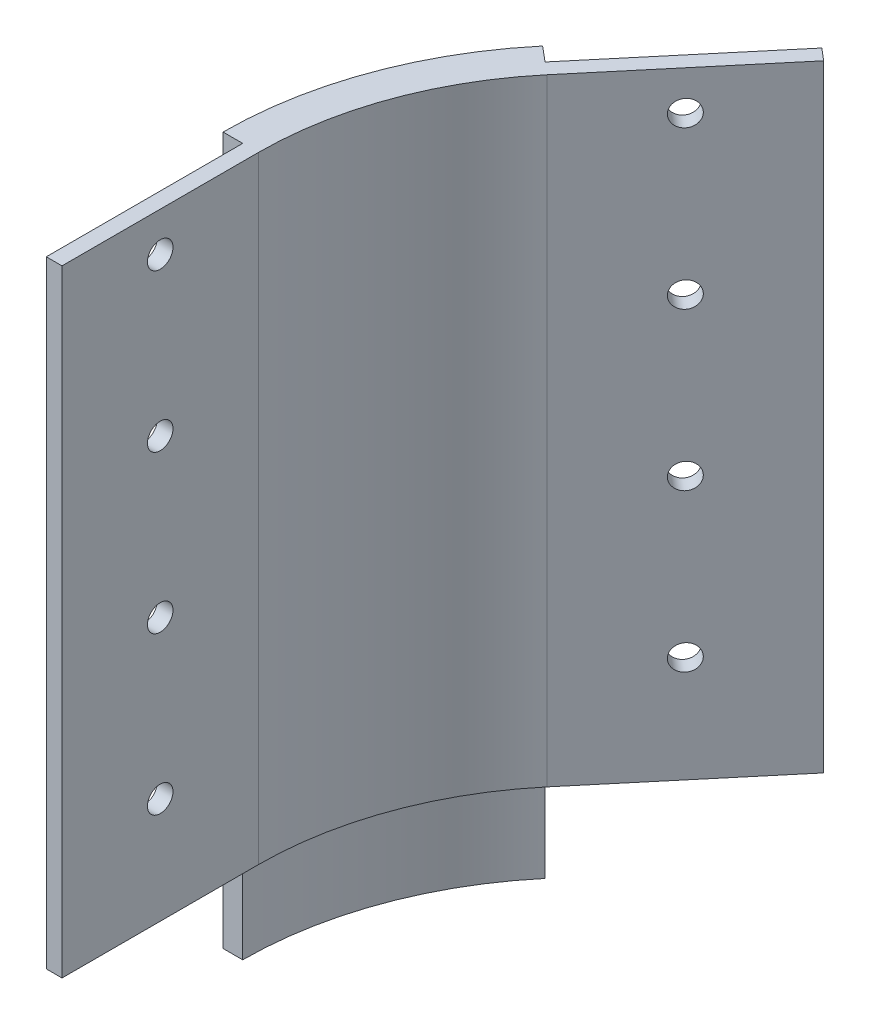
SolidWorks part; units mm, degrees
material "Custom Plastic"
ref_plane "Front Plane" through (0, 0, 0) normal (0, 0, 1) x (1, 0, 0)
ref_plane "Top Plane" through (0, 0, 0) normal (0, 1, 0) x (1, 0, 0)
ref_plane "Right Plane" through (0, 0, 0) normal (1, 0, 0) x (0, 0, -1)
sketch "Sketch1" plane through (0, 0, 0) normal (0, 1, 0) x (1, 0, 0)
  line L0 (0, 0) -> (65.2704, 0) construction
  line L1 (65.2704, 0) -> (65.2704, 50) construction
  line L2 (0, 0) -> (0, -10) construction
  line L3 (18.1985, 50) -> (-23.7565, 0) construction
  line L4 (10, 0) -> (-10, 0)
  line L5 (25.859, 43.5721) -> (10.5381, 56.4279)
  arc A0 (0, 0) -> (18.1985, 50) centre (77.7862, 0) cw construction
  arc A1 (10, 0) -> (25.859, 43.5721) centre (77.7862, 0) cw
  arc A2 (-10, 0) -> (10.5381, 56.4279) centre (77.7862, 0) cw
  circle A3 centre (0.6455, 10) radius 2.6
  circle A4 centre (4.6911, 26.6044) radius 2.6
  circle A5 centre (12.2651, 41.9247) radius 2.6
  circle A7 centre (23.0019, 55.2211) radius 2.6 [skipped]
  point P24 (77.7862, 0)
  dimension "D6" = 5.2
  dimension "D9" = 10
  dimension "D1" = 10
  dimension "D2" = 50
  dimension "D3" = 50
  dimension "D7" = 10
  dimension "D8" = 4
  dimension "D4" = 10
  dimension "D5" = 10
extrude "Boss-Extrude1" add sketch "Sketch1" along normal blind 20
sketch "Sketch2" plane through (0, 20, 0) normal (0, 1, 0) x (1, 0, 0)
  line L0 (6.7078, 59.6418) -> (10.5381, 56.4279)
  line L1 (-15, 0) -> (-10, 0)
  arc A1 (10.5381, 56.4279) -> (-10, 0) centre (77.7862, 0) ccw construction
  arc A2 (6.7078, 59.6418) -> (-15, 0) centre (77.7862, 0) ccw
  arc A3 (6.7078, 59.6418) -> (-15, 0) centre (77.7862, 0) ccw
  arc A4 (10.5381, 56.4279) -> (-10, 0) centre (77.7862, 0) ccw
  dimension "D1" = 5
extrude "Boss-Extrude2" add sketch "Sketch2" along normal blind 180 separate body
sketch "Sketch3" plane through (0, 20, 0) normal (0, 1, 0) x (1, 0, 0)
  line L2 (25.859, 43.5721) -> (10.5381, 56.4279)
  line L3 (-10, 0) -> (10, 0)
  line L4 (25.859, 43.5721) -> (10.5381, 56.4279)
  line L5 (-10, 0) -> (10, 0)
  arc A2 (25.859, 43.5721) -> (10, 0) centre (77.7862, 0) ccw
  arc A3 (10.5381, 56.4279) -> (-10, 0) centre (77.7862, 0) ccw
  arc A4 (25.859, 43.5721) -> (10, 0) centre (77.7862, 0) ccw
  arc A5 (10.5381, 56.4279) -> (-10, 0) centre (77.7862, 0) ccw
  dimension "D1" = 0
extrude "Cut-Extrude1" cut sketch "Sketch3" against normal through all
sketch "Sketch4" plane through (0, 200, 0) normal (0, 1, 0) x (1, 0, 0)
  line L0 (13.6022, 53.8567) -> (45.7416, 92.1589)
  line L1 (45.7416, 92.1589) -> (42.6774, 94.7301)
  line L2 (42.6774, 94.7301) -> (10.5381, 56.4279)
  line L3 (-0.9471, 28.6566) -> (-4.7058, 30.0246) construction
  line L4 (-6, 0) -> (-6, -50)
  line L5 (-6, -50) -> (-10, -50)
  line L6 (-10, -50) -> (-10, 0)
  arc A1 (10.5381, 56.4279) -> (-10, 0) centre (77.7862, 0) ccw construction
  arc A2 (13.6022, 53.8567) -> (-6, 0) centre (77.7862, 0) ccw
  arc A3 (13.6022, 53.8567) -> (-6, 0) centre (77.7862, 0) ccw
  arc M6 (-10, 0) -> (10.5381, 56.4279) centre (77.7862, 0) cw
  dimension "D2" = 50
  dimension "D1" = 4
extrude "Boss-Extrude3" add sketch "Sketch4" against normal up to surface (180 mm away) contours L3 A3 L0 L1 L2 M6 | A3 L3 L6 L5 L4 M6 up to face at (-4.4968, 20, -29.9486)
ref_plane "Plane1" through (9.0993, 0, -25) normal (0.342, 0, -0.9397) x (-0.9397, 0, -0.342)
sketch "Sketch5" plane through (-10, 0, 0) normal (-1, 0, 0) x (0, 0, 1)
  line L0 (25, 200) -> (25, 20) construction
  line L1 (50, 200) -> (0, 200) construction
  line L2 (0, 20) -> (50, 20) construction
  circle A0 centre (25, 190) radius 3.25
  circle A1 centre (25, 150) radius 3.25
  circle A2 centre (25, 110) radius 3.25
  circle A3 centre (25, 70) radius 3.25
  circle A4 centre (25, 30) radius 3.25
  dimension "D1" = 10
  dimension "D2" = 6.5
  dimension "D4" = 40
  dimension "D3" = 5
extrude "Cut-Extrude2" cut sketch "Sketch5" against normal through all
mirror "Mirror1" about plane through (9.0993, 0, -25) normal (0.342, 0, -0.9397) of "Cut-Extrude2"
sketch "Sketch7" plane through (0, 20, 0) normal (0, -1, 0) x (1, 0, 0)
  line L8 (6.7078, -59.6418) -> (10.5381, -56.4279)
  line L9 (10.5381, -56.4279) -> (42.6774, -94.7301)
  line L10 (42.6774, -94.7301) -> (45.7416, -92.1589)
  line L11 (45.7416, -92.1589) -> (13.6022, -53.8567)
  line L12 (-6, 0) -> (-6, 50)
  line L13 (-6, 50) -> (-10, 50)
  line L14 (-10, 50) -> (-10, 0)
  line L15 (-10, 0) -> (-15, 0)
  line L17 (10.5381, -56.4279) -> (42.6774, -94.7301)
  line L18 (42.6774, -94.7301) -> (45.7416, -92.1589)
  line L19 (45.7416, -92.1589) -> (13.6022, -53.8567)
  line L20 (-6, 0) -> (-6, 50)
  line L21 (-6, 50) -> (-10, 50)
  line L22 (-10, 50) -> (-10, 0)
  arc A0 (10.5381, -56.4279) -> (-10, 0) centre (77.7862, 0) cw
  arc A2 (-6, 0) -> (13.6022, -53.8567) centre (77.7862, 0) ccw
  arc A3 (-15, 0) -> (6.7078, -59.6418) centre (77.7862, 0) ccw
  arc A4 (-6, 0) -> (13.6022, -53.8567) centre (77.7862, 0) ccw
  dimension "D1" = 0
extrude "Cut-Extrude3" cut sketch "Sketch7" against normal blind 23
